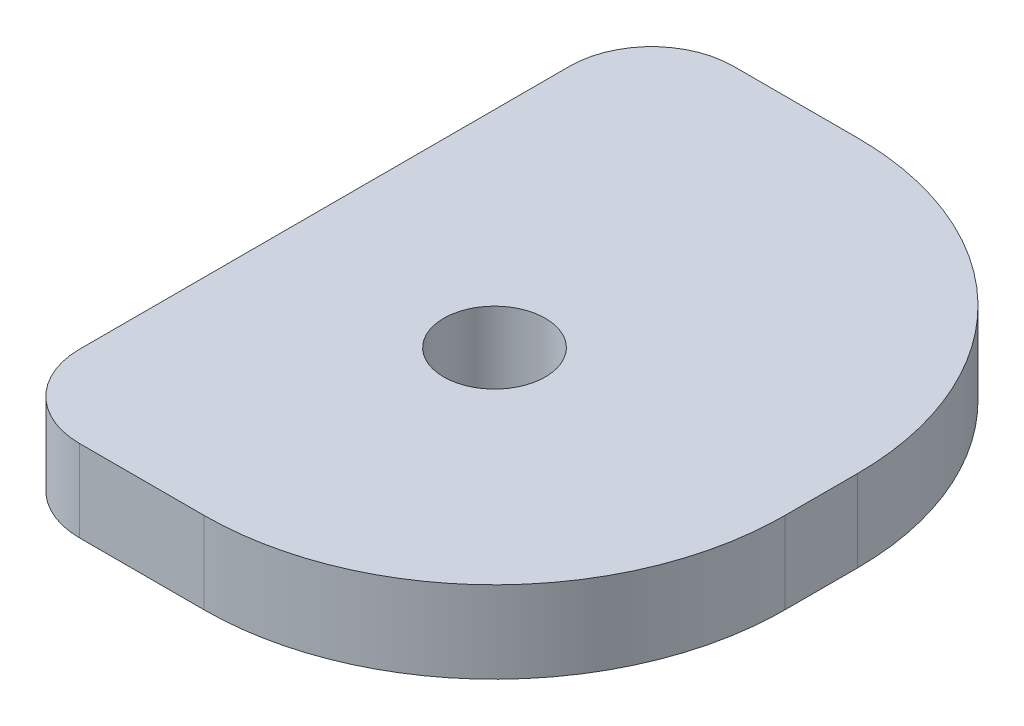
SolidWorks part; units mm, degrees
ref_plane "Front Plane" through (0, 0, 0) normal (0, 0, 1) x (1, 0, 0)
ref_plane "Top Plane" through (0, 0, 0) normal (0, 1, 0) x (1, 0, 0)
ref_plane "Right Plane" through (0, 0, 0) normal (1, 0, 0) x (0, 0, -1)
sketch "Sketch1" plane through (0, 0, 0) normal (0, 1, 0) x (1, 0, 0)
  line L1 (-25.4, 11.43) -> (25.4, 11.43)
  line L2 (-25.4, 11.43) -> (-25.4, -11.43)
  line L3 (-25.4, -11.43) -> (25.4, -11.43)
  line L4 (25.4, 11.43) -> (25.4, -11.43)
  dimension "D1" = 22.86
  dimension "D2" = 50.8
  dimension "D3" = 11.43
  dimension "D4" = 25.4
extrude "Boss-Extrude1" add sketch "Sketch1" along normal blind 3.175
fillet "Fillet1" radius 10.16 2 edges at (-25.4, 1.5875, 11.43) (25.4, 1.5875, 11.43)
sketch "Sketch3" plane through (0, 3.175, 0) normal (0, 1, 0) x (1, 0, 0)
  line L0 (-7.7526, -1.27) -> (18.5521, -1.27) construction
  circle A0 centre (15.24, -1.27) radius 1.778
  arc A2 (15.24, -11.43) -> (25.4, -1.27) centre (15.24, -1.27) ccw construction
  circle A3 centre (-3.81, -1.27) radius 1.778
  dimension "D1" = 3.556
  dimension "D6" = 3.556
  dimension "D5" = 19.05
extrude "Cut-Extrude1" cut sketch "Sketch3" against normal through all
fillet "Fillet3" radius 10.16 2 edges at (-25.4, 1.5875, -11.43) (25.4, 1.5875, -11.43)
scale "Scale1" scale about centroid uniform scaling no x scale factor 1.11 y scale factor 1 z scale factor 1.11
sketch "Sketch4" plane through (0, 3.175, 0) normal (0, 1, 0) x (1, 0, 0)
  line L1 (16.9283, 12.6847) -> (-16.9045, 12.6847) construction
  line L2 (8.9273, -8.3973) -> (8.9273, -1.8432) construction
  line L4 (-28.1821, 1.4071) -> (-28.1821, -1.4123) construction
  line L5 (8.9273, 12.6847) -> (-28.1821, 12.6847)
  line L6 (8.9273, 12.6847) -> (8.9273, -12.6899)
  line L7 (8.9273, -12.6899) -> (-28.1821, -12.6899)
  line L8 (-28.1821, 12.6847) -> (-28.1821, -12.6899)
  line L9 (-16.9045, -12.6899) -> (16.9283, -12.6899) construction
extrude "Cut-Extrude2" cut sketch "Sketch4" against normal through all contours L5 L8 L7 L6
fillet "Fillet4" radius 3.175 2 edges at (8.9273, 1.5875, 12.6899) (8.9273, 1.5875, -12.6847)
equation "\"D4@Sketch1\"=\"D2@Sketch1\"/2"
equation "\"D3@Sketch1\"=\"D1@Sketch1\"/2"
